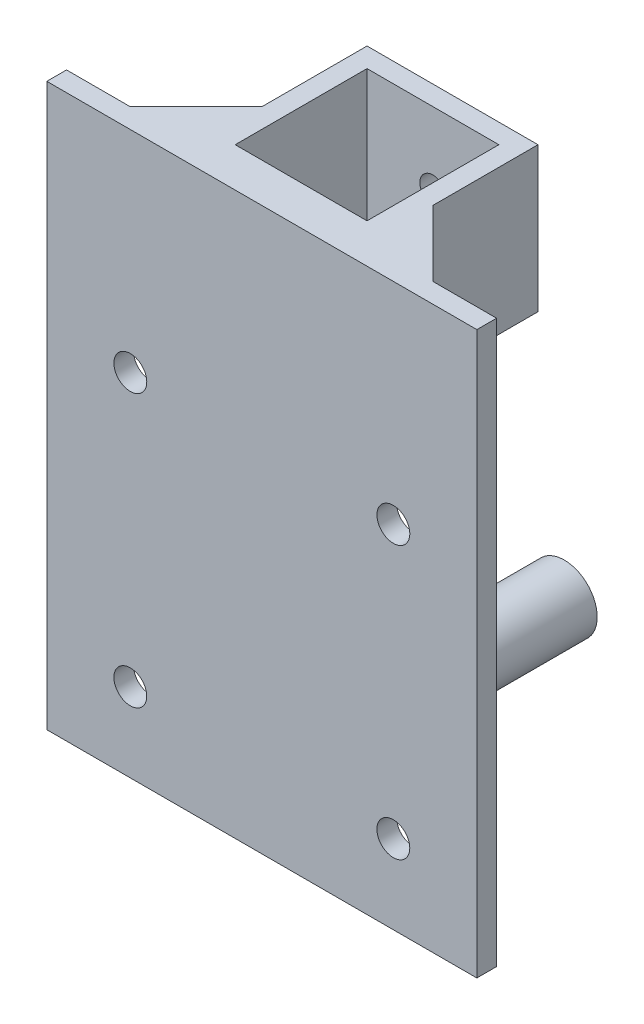
SolidWorks part; units mm, degrees
ref_plane "Спереди" through (0, 0, 0) normal (0, 0, 1) x (1, 0, 0)
ref_plane "Сверху" through (0, 0, 0) normal (0, 1, 0) x (1, 0, 0)
ref_plane "Справа" through (0, 0, 0) normal (1, 0, 0) x (0, 0, -1)
sketch "Эскиз1" plane through (0, 0, 0) normal (0, 0, 1) x (1, 0, 0)
  line L0 (-65.4, 53.4) -> (0, 53.4) construction
  line L1 (0, 0) -> (-65.4, 0)
  line L2 (0, 0) -> (0, 85.4)
  line L3 (0, 85.4) -> (-65.4, 85.4)
  line L4 (-65.4, 0) -> (-65.4, 85.4)
  line L5 (-32.7, 85.4) -> (-32.7, 0) construction
  circle A0 centre (-52.7, 53.4) radius 2.5
  circle A2 centre (-12.7, 53.4) radius 2.5
  circle A3 centre (-12.7, 12) radius 2.5
  circle A4 centre (-52.7, 12) radius 2.5
  dimension "D4" = 5
  dimension "D5" = 20
  dimension "D7" = 12
  dimension "D8" = 5
  dimension "D9" = 5
  dimension "D10" = 41.4
  dimension "D1" = 65.4
  dimension "D2" = 85.4
  dimension "D3" = 12
  dimension "D6" = 32
  dimension "D11" = 41.4
extrude "каретка" add sketch "Эскиз1" along normal blind 3
sketch "Эскиз2" plane through (0, 0, 0) normal (0, 0, -1) x (-1, 0, 0)
  line L0 (0, 85.4) -> (65.4, 85.4) construction
  line L1 (19.7, 85.4) -> (45.7, 85.4)
  line L2 (19.7, 85.4) -> (19.7, 63.4)
  line L3 (19.7, 63.4) -> (45.7, 63.4)
  line L4 (45.7, 85.4) -> (45.7, 63.4)
  line L5 (32.7, 85.4) -> (32.7, 0) construction
  line L6 (65.4, 0) -> (0, 0) construction
  point P10 (32.7, 85.4)
  dimension "D1" = 22
  dimension "D2" = 26
extrude "крепеж для направляющей" add sketch "Эскиз2" along normal blind 26
sketch "Эскиз3" plane through (0, 63.4, 0) normal (0, -1, 0) x (1, 0, 0)
  line L0 (-45.7, -13) -> (-19.7, -13) construction
  line L1 (-42.725, -2.975) -> (-22.675, -2.975)
  line L2 (-42.725, -2.975) -> (-42.725, -23.025)
  line L3 (-42.725, -23.025) -> (-22.675, -23.025)
  line L4 (-22.675, -2.975) -> (-22.675, -23.025)
  line L5 (-45.7, -26) -> (-45.7, 0) construction
  line L6 (-19.7, -26) -> (-19.7, 0) construction
  line L7 (-42.725, -13) -> (-22.675, -13) construction
  point P12 (-32.7, -13)
  point P13 (-32.7, -13)
  dimension "D1" = 20.05
  dimension "D2" = 20.05
extrude "дырка в крепеже для направляющей" cut sketch "Эскиз3" against normal through all
sketch "Эскиз4" plane through (0, 0, 0) normal (0, 0, -1) x (-1, 0, 0)
  line L0 (12.7, 53.4) -> (12.7, 12) construction
  line L1 (52.7, 53.4) -> (52.7, 12) construction
  circle A1 centre (52.7, 32.7) radius 2
  point P6 (52.7, 32.7)
  dimension "D1" = 4
sketch "Эскиз8" plane through (0, 0, 0) normal (0, 0, -1) x (-1, 0, 0)
  line L0 (12.7, 53.4) -> (12.7, 12) construction
  line L2 (65.4, 0) -> (0, 0) construction
  line L3 (65.4, 85.4) -> (65.4, 0) construction
  circle A0 centre (54.7, 32.7) radius 5.8726
  dimension "D1" = 11.7451
  dimension "D2" = 10.7
  dimension "D3" = 32.7
extrude "Бобышка-Вытянуть1" add sketch "Эскиз8" along normal blind 14.4
extrude "Бобышка-Вытянуть3" add sketch "Эскиз4" along normal blind 14.4 contours A1
sketch "Эскиз12" plane through (0, 0, 0) normal (0, 0, -1) x (-1, 0, 0)
  line L2 (65.4, 0) -> (0, 0) construction
  line L3 (0, 0) -> (0, 85.4) construction
  circle A0 centre (10.7, 32.7) radius 5
  dimension "D1" = 10
  dimension "D2" = 10.7
  dimension "D3" = 32.7
extrude "Бобышка-Вытянуть5" add sketch "Эскиз12" along normal blind 21 contours A0
sketch "Эскиз13" plane through (0, 0, -21) normal (0, 0, -1) x (-1, 0, 0)
  circle A0 centre (10.7, 32.7) radius 2
  dimension "D1" = 4
extrude "Вырез-Вытянуть1" cut sketch "Эскиз13" against normal blind 6.6
sketch "Эскиз14" plane through (0, 0, -14.4) normal (0, 0, -1) x (-1, 0, 0)
  line L1 (54.7, 38.5726) -> (54.7, 26.8274) construction
  circle A0 centre (54.7, 32.7) radius 2
  circle A3 centre (54.7, 32.7) radius 5.8726 construction
  circle A4 centre (54.7, 32.7) radius 5.8726 construction
  point P13 (54.7, 32.7)
  dimension "D1" = 4
extrude "Вырез-Вытянуть3" cut sketch "Эскиз14" against normal blind 8 contours A0
chamfer "Фаска1" distance 10 angle 45 1 edges at (-45.7, 74.4, 0)
chamfer "Фаска2" distance 10 angle 45 1 edges at (-19.7, 74.4, 0)
sketch "Эскиз15" plane through (0, 0, -26) normal (0, 0, -1) x (-1, 0, 0)
  line L0 (19.7, 85.4) -> (45.7, 63.4) construction
  circle A0 centre (32.7, 74.4) radius 2
  dimension "D1" = 4
extrude "Вырез-Вытянуть4" cut sketch "Эскиз15" against normal blind 8
